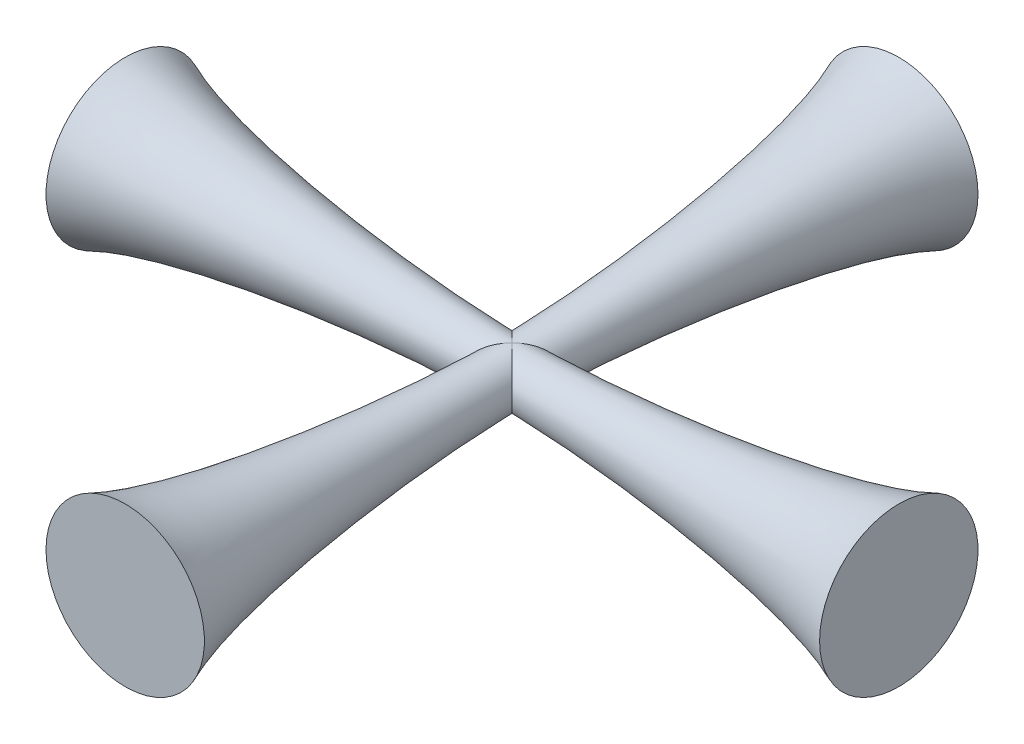
SolidWorks part; units mm, degrees
ref_plane "前视基准面" through (0, 0, 0) normal (0, 0, 1) x (1, 0, 0)
ref_plane "上视基准面" through (0, 0, 0) normal (0, 1, 0) x (1, 0, 0)
ref_plane "右视基准面" through (0, 0, 0) normal (1, 0, 0) x (0, 0, -1)
sketch "草图1" plane through (0, 0, 0) normal (0, 1, 0) x (1, 0, 0)
  line L0 (0, 0) -> (0, -36.7481)
  line L1 (0, -36.7481) -> (-7.5247, -36.7481)
  line L2 (0, 0) -> (-2.3956, 0)
  spline S0 degree 3 poles (-2.3956, 0) (-2.3956, -10.2699) (-4.2816, -29.2564) (-7.5247, -36.7481) knots 0 0 0 0 1 1 1 1
  point P6 (-2.9765, -18.7305)
  point P7 (-7.5247, -36.7481)
  point P8 (-2.9649, -11.9608)
revolve "旋转1" add sketch "草图1" angle 360 about L0
sketch "草图2" plane through (0, 0, 0) normal (1, 0, 0) x (0, 0, -1)
  line L0 (0, 5.4425) -> (0, -4.5933) construction
pattern_circular "阵列(圆周)3" count 4 over 360 about axis through (0, 5.4425, 0) along (0, -1, 0) of "旋转1"
